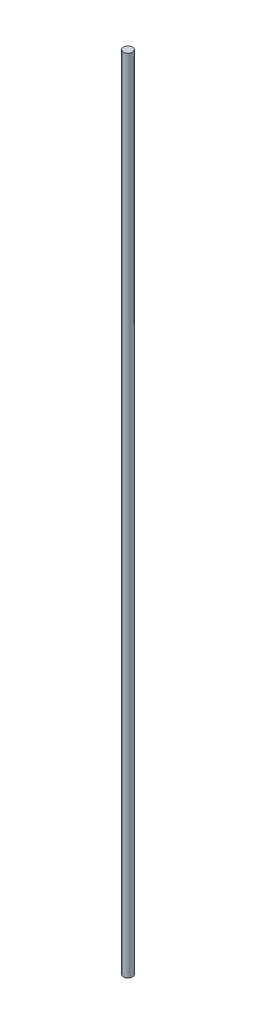
SolidWorks part; units mm, degrees
ref_plane "Front Plane" through (0, 0, 0) normal (1, 0, 0) x (0, 1, 0)
ref_plane "Top Plane" through (0, 0, 0) normal (0, 0, 1) x (0, 1, 0)
ref_plane "Right Plane" through (0, 0, 0) normal (0, 1, 0) x (-1, 0, 0)
sketch "Sketch1" plane through (0, 0, 0) normal (0, 1, 0) x (-1, 0, 0)
  circle A0 centre (0, 0) radius 3.1
  dimension "D1" = 6.2
extrude "Boss-Extrude1" add sketch "Sketch1" along normal blind 556
